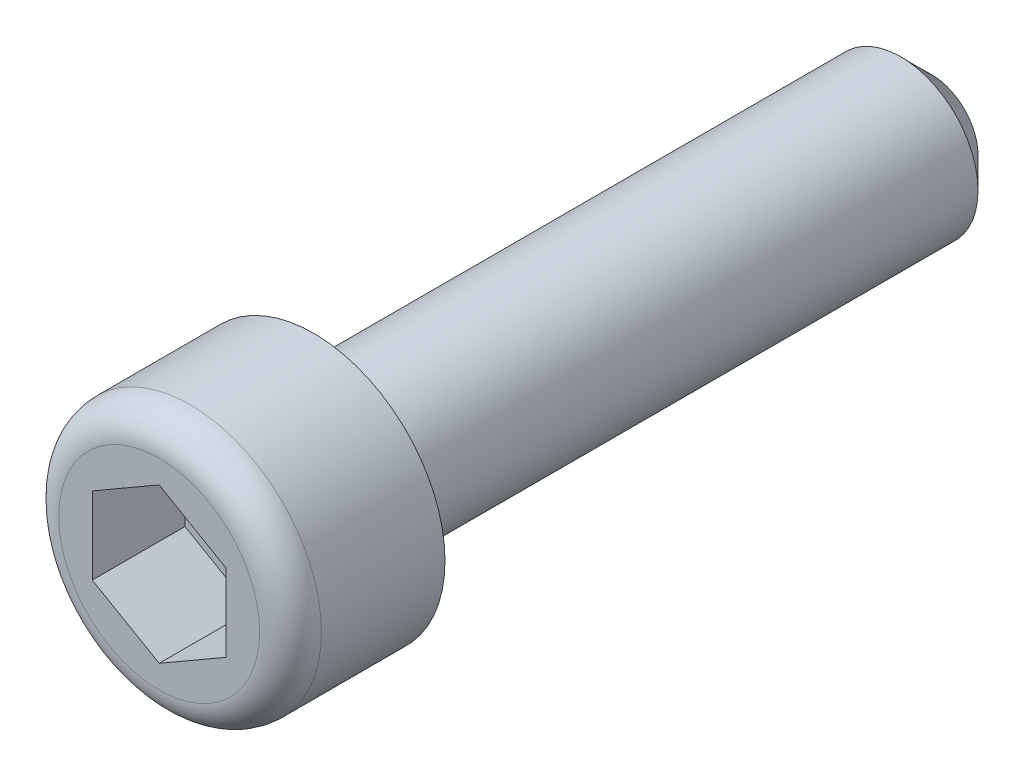
SolidWorks part; units mm, degrees
ref_plane "Front Plane" through (0, 0, 0) normal (0, 0, 1) x (1, 0, 0)
ref_plane "Top Plane" through (0, 0, 0) normal (0, 1, 0) x (1, 0, 0)
ref_plane "Right Plane" through (0, 0, 0) normal (1, 0, 0) x (0, 0, -1)
sketch "Sketch1" plane through (0, 0, 0) normal (1, 0, 0) x (0, 0, -1)
  line L0 (-156.2916, 0) -> (7658.2872, 0) construction
  line L1 (0, 0) -> (0, 4.25)
  line L2 (0, 4.25) -> (5, 4.25)
  line L3 (5, 4.25) -> (5, 2.5)
  line L4 (5, 2.5) -> (25, 2.5)
  line L5 (25, 2.5) -> (25, 0)
  line L6 (25, 0) -> (0, 0)
  dimension "D1" = 5
  dimension "D2" = 20
  dimension "D3" = 5
  dimension "D4" = 8.5
revolve "Body" add sketch "Sketch1" angle 360 about L0
sketch "Sketch2" plane through (0, 0, 0) normal (0, 0, 1) x (1, 0, 0)
  line L1 (0, 2.5) -> (-2.1651, 1.25)
  line L2 (-2.1651, 1.25) -> (-2.1651, -1.25)
  line L3 (-2.1651, -1.25) -> (0, -2.5)
  line L4 (0, -2.5) -> (2.1651, -1.25)
  line L5 (2.1651, -1.25) -> (2.1651, 1.25)
  line L6 (2.1651, 1.25) -> (0, 2.5)
  circle A0 centre (0, 0) radius 2.5 construction
  dimension "D1" = 5
extrude "Footprint" cut sketch "Sketch2" against normal blind 3
chamfer "Chamfer1" distance 1 angle 45 1 edges at (2.5, 0, -25)
fillet "Fillet1" radius 1 1 edges at (4.25, 0, 0)
